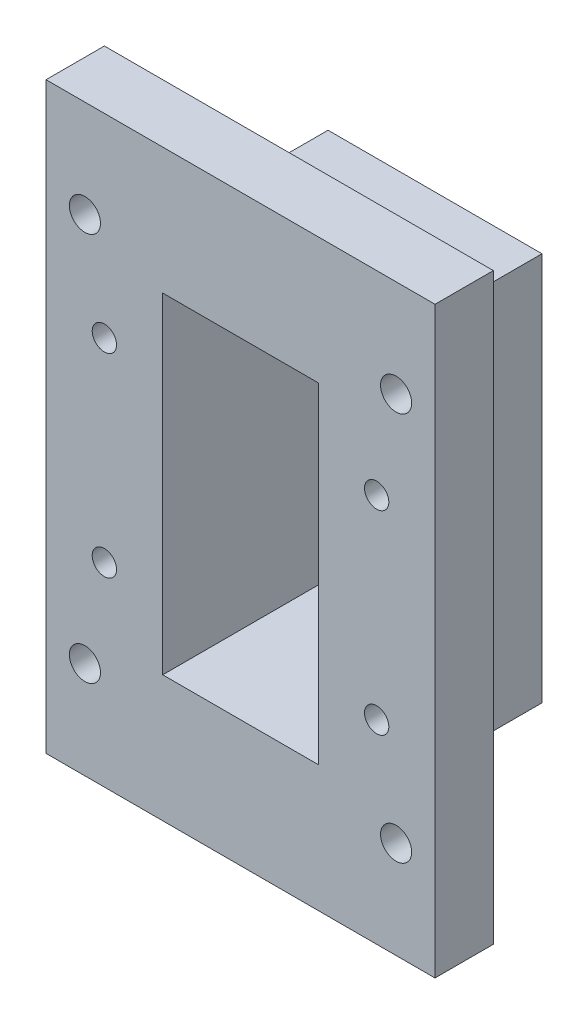
SolidWorks part; units mm, degrees
ref_plane "Front Plane" through (0, 0, 0) normal (0, 0, 1) x (1, 0, 0)
ref_plane "Top Plane" through (0, 0, 0) normal (0, 1, 0) x (1, 0, 0)
ref_plane "Right Plane" through (0, 0, 0) normal (1, 0, 0) x (0, 0, -1)
sketch "Sketch1" plane through (0, 0, 0) normal (0, 0, 1) x (1, 0, 0)
  line L1 (0, 0) -> (40, 0)
  line L2 (0, 0) -> (0, 60)
  line L3 (0, 60) -> (40, 60)
  line L4 (40, 0) -> (40, 60)
  dimension "D1" = 40
  dimension "D2" = 60
extrude "Boss-Extrude1" add sketch "Sketch1" along normal blind 6
sketch "Sketch2" plane through (0, 0, 6) normal (0, 0, 1) x (1, 0, 0)
  line L0 (20, 60) -> (20, 0) construction
  line L1 (40, 60) -> (0, 60) construction
  line L3 (4, 60) -> (4, -4.376) construction
  line L4 (36, 60) -> (36, -4.376) construction
  line L5 (20, 60) -> (20, -4.376) construction
  line L6 (0, 0) -> (40, 0) construction
  point P10 (4, 50)
  point P18 (20, 30)
  point P24 (36, 50)
  point P25 (36, 10)
  point P26 (4, 10)
  dimension "D1" = 16
  dimension "D3" = 20
  dimension "D2" = 16
  dimension "D4" = 2
  dimension "D5" = 2
hole_wizard "M3 Clearance Hole1" positions "Sketch2" profile "Sketch3" hole size "M3" standard "DIN" end condition up to next
sketch "Sketch3" plane through (4, 10, 6) normal (1, 0, 0) x (0, -1, 0)
  line L0 (0, 0) -> (0, 6)
  line L1 (0, 6) -> (1.6, 6)
  line L2 (1.6, 6) -> (1.6, 0)
  line L5 (1.6, 0) -> (0, 0)
  line L11 (0, -6.35) -> (0, 107.95) construction
  dimension "Thru Hole Dia." = 3.2
  dimension "Thru Hole Depth" = 6
sketch "Sketch4" plane through (0, 0, 6) normal (0, 0, 1) x (1, 0, 0)
  line L1 (9, 50) -> (31, 50)
  line L2 (9, 50) -> (9, 10)
  line L3 (9, 10) -> (31, 10)
  line L4 (31, 50) -> (31, 10)
  line L5 (20, 60) -> (20, 50) construction
  line L6 (40, 60) -> (0, 60) construction
  line L7 (9, 30) -> (0, 30) construction
  line L8 (0, 60) -> (0, 0) construction
  dimension "D1" = 22
  dimension "D2" = 40
extrude "Cut-Extrude1" cut sketch "Sketch4" against normal through all and the other way through all
sketch "Sketch6" plane through (0, 0, 6) normal (0, 0, -1) x (-1, 0, 0)
  line L16 (-9, 10) -> (-31, 10) construction
  line L17 (-31, 10) -> (-31, 50) construction
  line L18 (-31, 50) -> (-9, 50) construction
  line L19 (-9, 50) -> (-9, 10) construction
  line L20 (-9, 10) -> (-31, 10)
  line L21 (-31, 10) -> (-31, 50)
  line L22 (-31, 50) -> (-9, 50)
  line L23 (-9, 50) -> (-9, 10)
  line L24 (-12, 13) -> (-28, 13)
  line L25 (-28, 13) -> (-28, 47)
  line L26 (-28, 47) -> (-12, 47)
  line L27 (-12, 47) -> (-12, 13)
  dimension "D1" = 3
extrude "Boss-Extrude2" add sketch "Sketch6" along normal blind 20
sketch "Sketch8" plane through (0, 0, 6) normal (0, 0, 1) x (1, 0, 0)
  line L0 (20, 47) -> (20, -9.9171) construction
  line L1 (12, 47) -> (28, 47) construction
  line L3 (12, 30) -> (0, 30) construction
  line L4 (12, 13) -> (12, 47) construction
  line L5 (0, 60) -> (0, 0) construction
  line L7 (6, 45.1036) -> (6, 16.9125) construction
  point P17 (6, 40)
  point P20 (0, 0)
  point P21 (6, 20)
  point P22 (0, 0)
  point P23 (34, 20)
  point P24 (34, 40)
  dimension "D1" = 10
hole_wizard "Tap Drill for M3 Tap2" positions "Sketch8" profile "Sketch9" hole size "M3" standard "DIN" end condition up to next
sketch "Sketch9" plane through (34, 40, 6) normal (1, 0, 0) x (0, -1, 0)
  line L0 (0, 0) -> (0, 6)
  line L1 (0, 6) -> (1.25, 6)
  line L2 (1.25, 6) -> (1.25, 0)
  line L5 (1.25, 0) -> (0, 0)
  line L11 (0, -6.35) -> (0, 107.95) construction
  dimension "Thru Hole Dia." = 2.5
  dimension "Thru Hole Depth" = 6
